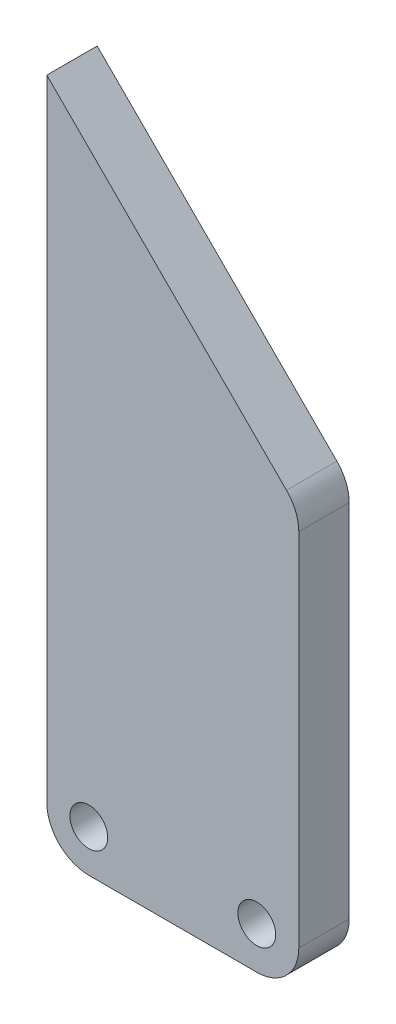
SolidWorks part; units mm, degrees
material "6061-T6 (SS)"
ref_plane "Alzado" through (0, 0, 0) normal (0, 0, 1) x (1, 0, 0)
ref_plane "Planta" through (0, 0, 0) normal (0, 1, 0) x (1, 0, 0)
ref_plane "Vista lateral" through (0, 0, 0) normal (1, 0, 0) x (0, 0, -1)
sketch "Croquis1" plane through (0, 0, 0) normal (0, 0, 1) x (1, 0, 0)
  line L0 (0, 0) -> (0, 80)
  line L1 (0, 80) -> (30, 50)
  line L2 (30, 50) -> (30, 0)
  line L3 (30, 0) -> (0, 0)
  dimension "D1" = 30
  dimension "D2" = 90
  dimension "D3" = 45
  dimension "D4" = 80
extrude "Saliente-Extruir1" add sketch "Croquis1" along normal mid plane 6
hole_wizard "Taladro de margen para M41" positions "Croquis2" profile "Croquis3" hole size "M4" standard "Ansi Metric" end condition up to next
sketch "Croquis2" plane through (0, 0, 3) normal (0, 0, 1) x (1, 0, 0)
  line L0 (0, 80) -> (0, 0) construction
  line L1 (0, 0) -> (30, 0) construction
  point P0 (5, 5)
  point P2 (25, 5)
  dimension "D1" = 20
  dimension "D2" = 5
  dimension "D3" = 5
sketch "Croquis3" plane through (5, 5, 3) normal (1, 0, 0) x (0, -1, 0)
  line L0 (0, 0) -> (0, 6)
  line L1 (0, 6) -> (2.25, 6)
  line L2 (2.25, 6) -> (2.25, 0)
  line L5 (2.25, 0) -> (0, 0)
  line L11 (0, -6.35) -> (0, 107.95) construction
  dimension "Diámetro de taladro hasta el siguiente" = 4.5
  dimension "Profundidad de taladro hasta el siguiente" = 6
fillet "Redondeo1" radius 5 3 edges at (30, 50, 0) (0, 0, 0) (30, 0, 0)
